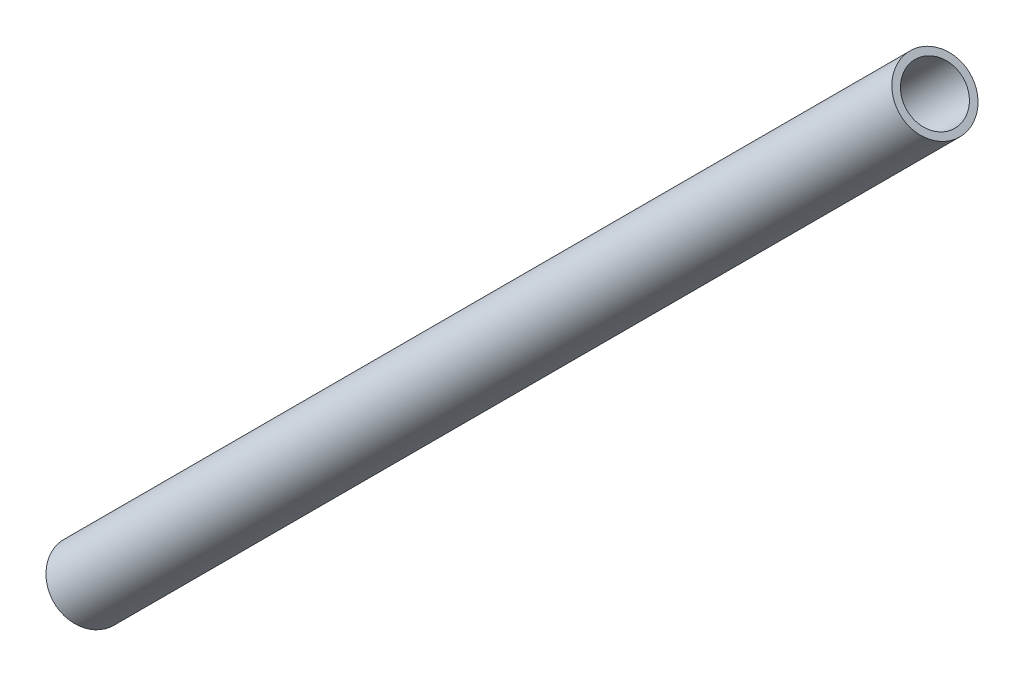
SolidWorks part; units mm, degrees
ref_plane "Front Plane" through (0, 0, 0) normal (0, 0, 1) x (1, 0, 0)
ref_plane "Top Plane" through (0, 0, 0) normal (0, 1, 0) x (1, 0, 0)
ref_plane "Right Plane" through (0, 0, 0) normal (1, 0, 0) x (0, 0, -1)
sketch "Sketch2" plane through (94.8593, 94.8593, 0) normal (-0.7071, -0.7071, 0) x (0, 0, 1)
  circle A0 centre (-10, -38.4567) radius 4
  circle A1 centre (-10, -38.4567) radius 5
  circle A2 centre (-10, -38.4567) radius 5
  dimension "D1" = 0
  dimension "D2" = 1
extrude "Boss-Extrude1" add sketch "Sketch2" along normal blind 170
